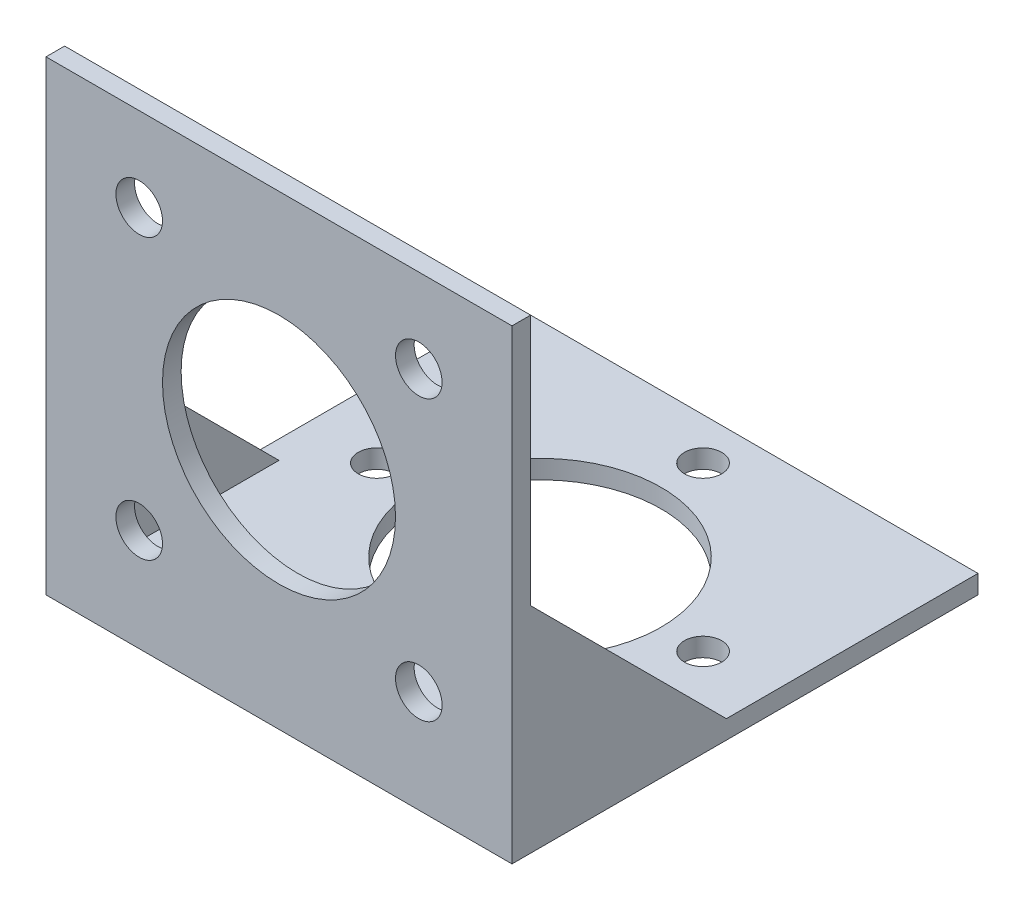
SolidWorks part; units mm, degrees
material "6061 合金"
ref_plane "前视基准面" through (0, 0, 0) normal (0, 0, 1) x (1, 0, 0)
ref_plane "上视基准面" through (0, 0, 0) normal (0, 1, 0) x (1, 0, 0)
ref_plane "右视基准面" through (0, 0, 0) normal (1, 0, 0) x (0, 0, -1)
other "Configuration Table"
sketch "草图1" plane through (0, 0, 0) normal (0, 1, 0) x (1, 0, 0)
  line L1 (-25, 25) -> (25, 25)
  line L2 (-25, 25) -> (-25, -25)
  line L3 (-25, -25) -> (25, -25)
  line L4 (25, 25) -> (25, -25)
  line L5 (-25, 25) -> (25, -25) construction
  line L6 (-25, -25) -> (25, 25) construction
  circle A0 centre (0, 3) radius 13
  circle A1 centre (0, 3) radius 17.5 construction
  circle A2 centre (0, 20.5) radius 2
  circle A3 centre (0, -14.5) radius 2
  circle A4 centre (17.5, 3) radius 2
  circle A5 centre (-17.5, 3) radius 2
  point P0 (0, 0)
  dimension "D4" = 26
  dimension "D5" = 35
  dimension "D6" = 4
  dimension "D1" = 50
  dimension "D2" = 50
  dimension "D3" = 28
extrude "凸台-拉伸1" add sketch "草图1" along normal blind 2
sketch "草图2" plane through (0, 0, 25) normal (0, 0, 1) x (1, 0, 0)
  line L0 (25, 2) -> (25, 0) construction
  line L1 (-25, 0) -> (25, 0)
  line L2 (-25, 0) -> (-25, 50)
  line L3 (-25, 50) -> (25, 50)
  line L4 (25, 0) -> (25, 50)
  line L6 (-15, 41) -> (15, 41) construction
  line L7 (-15, 41) -> (-15, 11) construction
  line L8 (-15, 11) -> (15, 11) construction
  line L9 (15, 41) -> (15, 11) construction
  line L10 (-15, 41) -> (15, 11) construction
  line L11 (-15, 11) -> (15, 41) construction
  circle A0 centre (0, 26) radius 12.5
  circle A3 centre (-15, 41) radius 2.5
  circle A4 centre (15, 41) radius 2.5
  circle A5 centre (15, 11) radius 2.5
  circle A6 centre (-15, 11) radius 2.5
  dimension "D3" = 25
  dimension "D4" = 30
  dimension "D6" = 5
  dimension "D1" = 50
  dimension "D2" = 26
  dimension "D5" = 30
extrude "凸台-拉伸2" add sketch "草图2" against normal blind 2
sketch "草图3" plane through (25, 0, 0) normal (1, 0, 0) x (0, 0, -1)
  line L0 (-25, 0) -> (0, 0)
  line L1 (-25, 0) -> (25, 0) construction
  line L2 (0, 0) -> (-25, 25)
  line L3 (-25, 50) -> (-25, 0) construction
  line L4 (-25, 25) -> (-25, 0)
  dimension "D1" = 45
extrude "凸台-拉伸3" add sketch "草图3" against normal blind 2
mirror "镜向2" about plane through (0, 0, 0) normal (1, 0, 0) of "凸台-拉伸3"
